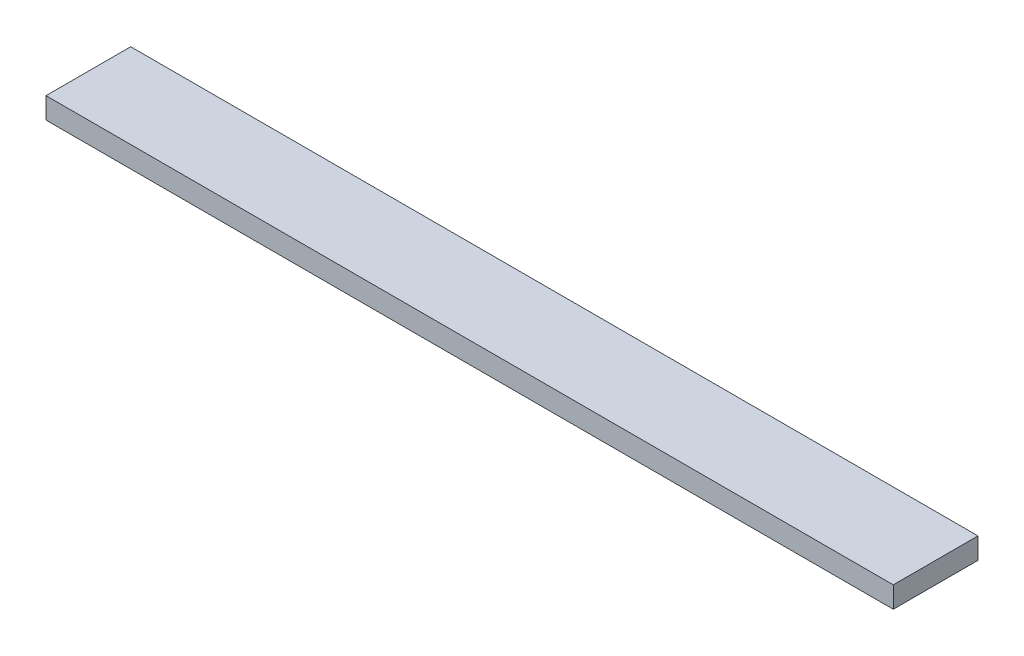
SolidWorks part; units mm, degrees
ref_plane "Front Plane" through (0, 0, 0) normal (0, 0, 1) x (1, 0, 0)
ref_plane "Top Plane" through (0, 0, 0) normal (0, 1, 0) x (1, 0, 0)
ref_plane "Right Plane" through (0, 0, 0) normal (1, 0, 0) x (0, 0, -1)
sketch "Sketch1" plane through (0, 0, 0) normal (0, 0, 1) x (1, 0, 0)
  line L0 (-200, 200) -> (200, 200)
  line L3 (-200, 200) -> (-200, 190)
  line L4 (200, 200) -> (-200, 200) construction
  line L5 (200, 200) -> (200, 190)
  line L6 (200, -200) -> (200, 200) construction
  line L7 (200, 190) -> (-200, 190)
  dimension "D2" = 10
extrude "Boss-Extrude1" add sketch "Sketch1" along normal blind 40
